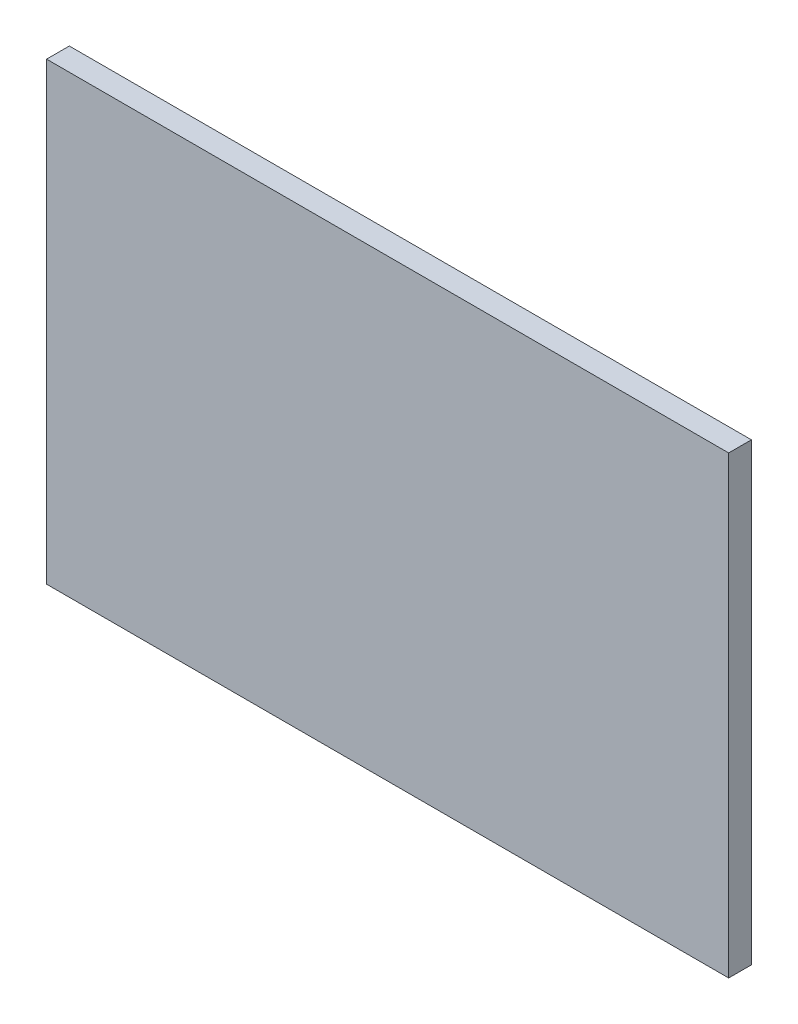
SolidWorks part; units mm, degrees
ref_plane "Front Plane" through (0, 0, 0) normal (0, 0, 1) x (1, 0, 0)
ref_plane "Top Plane" through (0, 0, 0) normal (0, 1, 0) x (1, 0, 0)
ref_plane "Right Plane" through (0, 0, 0) normal (1, 0, 0) x (0, 0, -1)
sketch "Esquisse1" plane through (0, 0, 0) normal (0, 0, 1) x (1, 0, 0)
  line L1 (-30, -20) -> (30, -20)
  line L2 (-30, -20) -> (-30, 20)
  line L3 (-30, 20) -> (30, 20)
  line L4 (30, -20) -> (30, 20)
  line L5 (-30, -20) -> (30, 20) construction
  line L6 (-30, 20) -> (30, -20) construction
  point P0 (0, 0)
  dimension "D1" = 40
  dimension "D2" = 60
extrude "Boss.-Extru.1" add sketch "Esquisse1" along normal blind 2
